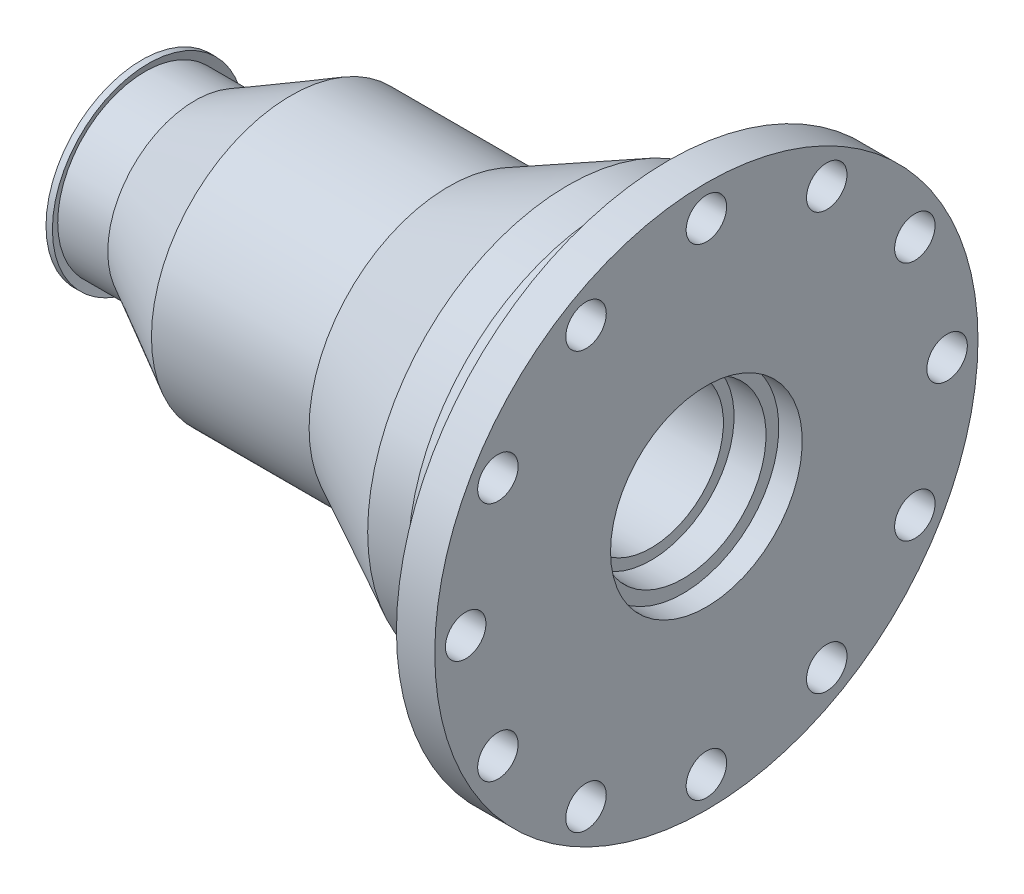
SolidWorks part; units mm, degrees
ref_plane "Спереди" through (0, 0, 0) normal (0, 0, 1) x (1, 0, 0)
ref_plane "Сверху" through (0, 0, 0) normal (0, 1, 0) x (1, 0, 0)
ref_plane "Справа" through (0, 0, 0) normal (1, 0, 0) x (0, 0, -1)
sketch "Эскиз1" plane through (0, 0, 0) normal (0, 0, 1) x (1, 0, 0)
  line L0 (0, 0) -> (265, 0)
  line L1 (0, 0) -> (0, 45)
  line L2 (0, 45) -> (3, 45)
  line L3 (3, 45) -> (1.5, 41)
  line L4 (1.5, 41) -> (25, 41)
  line L5 (25, 41) -> (70, 65.5)
  line L6 (70, 65.5) -> (144, 65.5)
  line L7 (144, 65.5) -> (200, 94)
  line L8 (200, 94) -> (220, 94)
  line L9 (220, 94) -> (220, 95)
  line L10 (220, 95) -> (239, 95)
  line L11 (239, 95) -> (239, 100)
  line L12 (239, 100) -> (247, 100)
  line L13 (247, 100) -> (247, 127.5)
  line L14 (247, 127.5) -> (265, 127.5)
  line L15 (265, 127.5) -> (265, 0)
revolve "Повернуть1" add sketch "Эскиз1" angle 360 about L0
sketch "Эскиз2" plane through (0, 0, 0) normal (0, 0, 1) x (1, 0, 0)
  line L0 (0, 0) -> (265, 0)
  line L1 (265, -127.5) -> (265, 127.5) construction
  line L2 (0, 0) -> (0, 31)
  line L3 (0, 45) -> (0, -45) construction
  line L4 (0, 31) -> (203.5, 31)
  line L5 (203.5, 31) -> (203.5, 34)
  line L6 (203.5, 34) -> (239, 34)
  line L7 (239, 100) -> (239, -100) construction
  line L8 (239, 34) -> (239, 39)
  line L9 (239, 39) -> (254, 39)
  line L10 (254, 39) -> (254, 45)
  line L11 (254, 45) -> (265, 45)
  line L12 (265, 45) -> (265, 0)
revolve "Вырез-Повернуть1" cut sketch "Эскиз2" angle 360 about L0
sketch "Эскиз3" plane through (0, 0, 0) normal (1, 0, 0) x (0, 0, -1)
  circle A0 centre (0, 113) radius 9.5
extrude "Вырез-Вытянуть1" cut sketch "Эскиз3" along normal through all
sketch "Эскиз4" plane through (0, 0, 0) normal (1, 0, 0) x (0, 0, -1)
  circle A0 centre (-56.5, 97.8609) radius 9.5
extrude "Вырез-Вытянуть2" cut sketch "Эскиз4" along normal through all
sketch "Эскиз5" plane through (0, 0, 0) normal (1, 0, 0) x (0, 0, -1)
  circle A0 centre (-97.8609, 56.5) radius 9.5
extrude "Вырез-Вытянуть3" cut sketch "Эскиз5" along normal through all
sketch "Эскиз6" plane through (0, 0, 0) normal (1, 0, 0) x (0, 0, -1)
  circle A0 centre (-113, 0) radius 9.5
extrude "Вырез-Вытянуть4" cut sketch "Эскиз6" along normal through all
sketch "Эскиз7" plane through (0, 0, 0) normal (1, 0, 0) x (0, 0, -1)
  circle A0 centre (-97.8609, -56.5) radius 9.5
extrude "Вырез-Вытянуть5" cut sketch "Эскиз7" along normal through all
sketch "Эскиз8" plane through (0, 0, 0) normal (1, 0, 0) x (0, 0, -1)
  circle A0 centre (-56.5, -97.8609) radius 9.5
extrude "Вырез-Вытянуть6" cut sketch "Эскиз8" along normal through all
sketch "Эскиз9" plane through (0, 0, 0) normal (1, 0, 0) x (0, 0, -1)
  circle A0 centre (0, -113) radius 9.5
extrude "Вырез-Вытянуть7" cut sketch "Эскиз9" along normal through all
sketch "Эскиз10" plane through (0, 0, 0) normal (1, 0, 0) x (0, 0, -1)
  circle A0 centre (56.5, -97.8609) radius 9.5
extrude "Вырез-Вытянуть8" cut sketch "Эскиз10" along normal through all
sketch "Эскиз11" plane through (0, 0, 0) normal (1, 0, 0) x (0, 0, -1)
  circle A0 centre (97.8609, -56.5) radius 9.5
extrude "Вырез-Вытянуть9" cut sketch "Эскиз11" along normal through all
sketch "Эскиз12" plane through (0, 0, 0) normal (1, 0, 0) x (0, 0, -1)
  circle A0 centre (113, 0) radius 9.5
extrude "Вырез-Вытянуть10" cut sketch "Эскиз12" along normal through all
sketch "Эскиз13" plane through (0, 0, 0) normal (1, 0, 0) x (0, 0, -1)
  circle A0 centre (97.8609, 56.5) radius 9.5
extrude "Вырез-Вытянуть11" cut sketch "Эскиз13" along normal through all
sketch "Эскиз14" plane through (0, 0, 0) normal (1, 0, 0) x (0, 0, -1)
  circle A0 centre (56.5, 97.8609) radius 9.5
extrude "Вырез-Вытянуть12" cut sketch "Эскиз14" along normal through all
